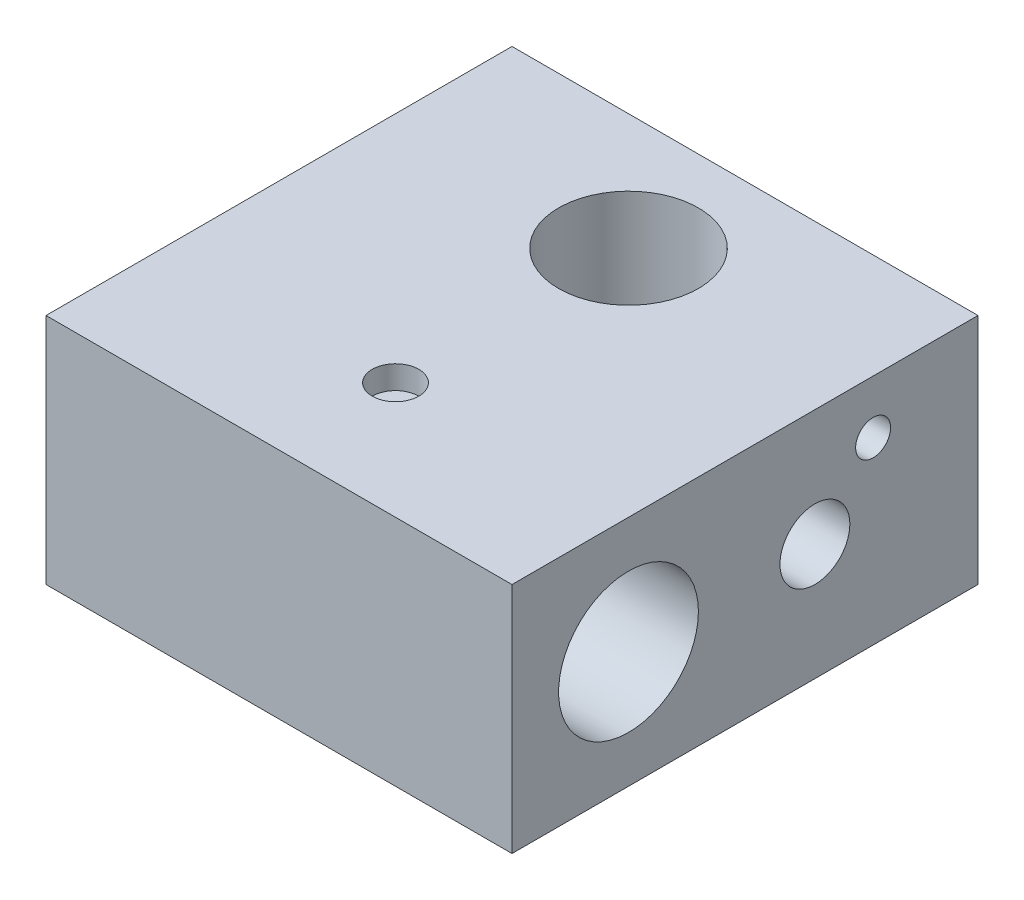
SolidWorks part; units mm, degrees
ref_plane "Ön Düzlem" through (0, 0, 0) normal (0, 0, 1) x (1, 0, 0)
ref_plane "Üst Düzlem" through (0, 0, 0) normal (0, 1, 0) x (1, 0, 0)
ref_plane "Sağ Düzlem" through (0, 0, 0) normal (1, 0, 0) x (0, 0, -1)
sketch "Sketch1" plane through (0, 0, 0) normal (0, 0, 1) x (1, 0, 0)
  line L1 (-10, -5) -> (10, -5)
  line L2 (-10, -5) -> (-10, 5)
  line L3 (-10, 5) -> (10, 5)
  line L4 (10, -5) -> (10, 5)
  line L5 (-10, -5) -> (10, 5) construction
  line L6 (-10, 5) -> (10, -5) construction
  point P0 (0, 0)
  dimension "D1" = 20
  dimension "D2" = 10
extrude "Boss-Extrude1" add sketch "Sketch1" along normal blind 20
sketch "Sketch3" plane through (0, 5, 0) normal (0, 1, 0) x (1, 0, 0)
  circle A0 centre (0, -5) radius 3
  dimension "D1" = 6
  dimension "D3" = 5
extrude "Cut-Extrude1" cut sketch "Sketch3" against normal blind 10
sketch "Sketch4" plane through (0, 5, 0) normal (0, 1, 0) x (1, 0, 0)
  circle A0 centre (0, -15) radius 1
  circle A1 centre (0, -5) radius 3 construction
  dimension "D2" = 2
  dimension "D1" = 10
extrude "Cut-Extrude2" cut sketch "Sketch4" against normal blind 1
sketch "Sketch7" plane through (10, 0, 0) normal (1, 0, 0) x (0, 0, -1)
  circle A0 centre (-15, 0) radius 3
  dimension "D2" = 6
  dimension "D1" = 15
extrude "Cut-Extrude10" cut sketch "Sketch7" against normal blind 20
sketch "Sketch8" plane through (10, 0, 0) normal (1, 0, 0) x (0, 0, -1)
  line L0 (0, -5) -> (0, 5) construction
  circle A0 centre (-7, 0) radius 1.5
  circle A1 centre (-4.5019, 2.7101) radius 0.75
  point P5 (0, 0)
  dimension "D1" = 3
  dimension "D3" = 1.5
  dimension "D2" = 7
extrude "Cut-Extrude11" cut sketch "Sketch8" against normal blind 4
